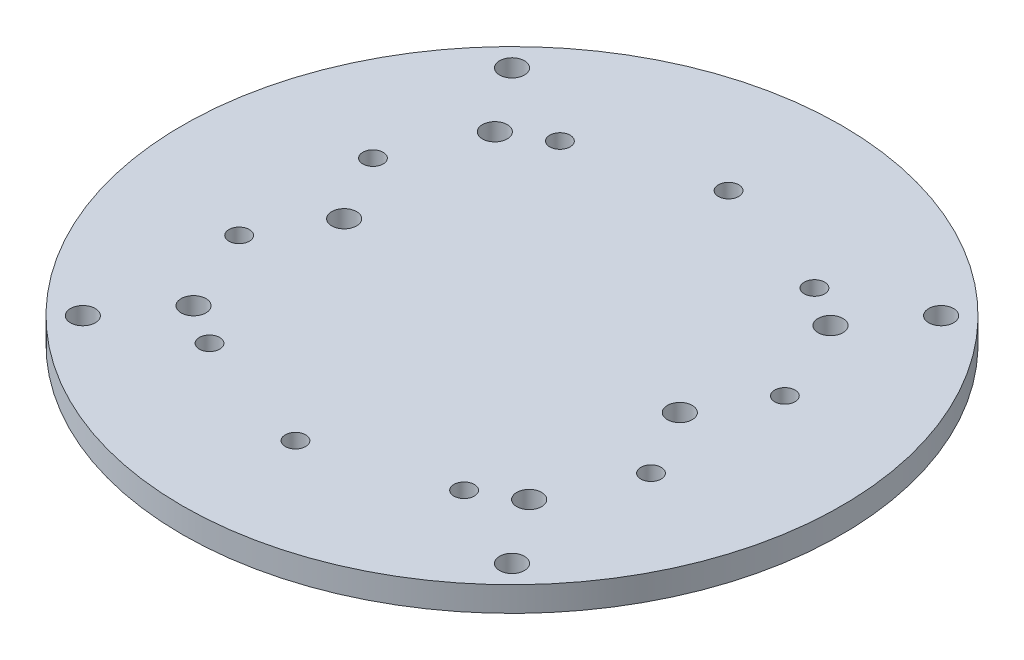
SolidWorks part; units mm, degrees
ref_plane "Front Plane" through (0, 0, 0) normal (0, 0, 1) x (1, 0, 0)
ref_plane "Top Plane" through (0, 0, 0) normal (0, 1, 0) x (1, 0, 0)
ref_plane "Right Plane" through (0, 0, 0) normal (1, 0, 0) x (0, 0, -1)
sketch "Sketch1" plane through (0, -66.8, 0) normal (0, -1, 0) x (1, 0, 0)
  circle A1 centre (0, 0) radius 84.1675 construction
  circle A3 centre (54.8008, 54.8008) radius 3.175
  circle A4 centre (54.8008, -54.8008) radius 3.175
  circle A5 centre (-54.8008, -54.8008) radius 3.175
  circle A6 centre (-54.8008, 54.8008) radius 3.175
  circle A7 centre (42.8625, -38.4762) radius 2.6035 construction
  circle A8 centre (42.8625, 0) radius 2.6035 construction
  circle A9 centre (42.8625, 38.4762) radius 2.6035 construction
  circle A10 centre (-42.8625, 38.4762) radius 2.6035 construction
  circle A11 centre (-42.8625, 0) radius 2.6035 construction
  circle A12 centre (-42.8625, -38.4762) radius 2.6035 construction
  circle A13 centre (42.8625, -38.4762) radius 2.6035 construction
  circle A14 centre (42.8625, 0) radius 2.6035 construction
  circle A15 centre (42.8625, 38.4762) radius 2.6035 construction
  circle A16 centre (-42.8625, 38.4762) radius 2.6035 construction
  circle A17 centre (-42.8625, 0) radius 2.6035 construction
  circle A18 centre (-42.8625, -38.4762) radius 2.6035 construction
  circle A19 centre (-42.8625, -38.4762) radius 3.175
  circle A20 centre (-42.8625, 0) radius 3.175
  circle A21 centre (-42.8625, 38.4762) radius 3.175
  circle A22 centre (42.8625, 38.4762) radius 3.175
  circle A23 centre (42.8625, 0) radius 3.175
  circle A24 centre (42.8625, -38.4762) radius 3.175
  circle A25 centre (-52.5982, -17.0902) radius 3.175 construction
  circle A26 centre (-52.5982, 17.0902) radius 3.175 construction
  circle A27 centre (-32.5075, 44.7427) radius 3.175 construction
  circle A28 centre (0, 55.305) radius 3.175 construction
  circle A29 centre (32.5075, 44.7427) radius 3.175 construction
  circle A30 centre (52.5982, 17.0902) radius 3.175 construction
  circle A31 centre (52.5982, -17.0902) radius 3.175 construction
  circle A32 centre (32.5075, -44.7427) radius 3.175 construction
  circle A33 centre (0, -55.305) radius 3.175 construction
  circle A34 centre (-32.5075, -44.7427) radius 3.175 construction
  circle A35 centre (-52.5982, -17.0902) radius 3.175 construction
  circle A36 centre (-52.5982, 17.0902) radius 3.175 construction
  circle A37 centre (-32.5075, 44.7427) radius 3.175 construction
  circle A38 centre (0, 55.305) radius 3.175 construction
  circle A39 centre (32.5075, 44.7427) radius 3.175 construction
  circle A40 centre (52.5982, 17.0902) radius 3.175 construction
  circle A41 centre (52.5982, -17.0902) radius 3.175 construction
  circle A42 centre (32.5075, -44.7427) radius 3.175 construction
  circle A43 centre (0, -55.305) radius 3.175 construction
  circle A44 centre (-32.5075, -44.7427) radius 3.175 construction
  circle A45 centre (-52.5982, -17.0902) radius 2.6035
  circle A46 centre (-52.5982, 17.0902) radius 2.6035
  circle A47 centre (-32.5075, 44.7427) radius 2.6035
  circle A48 centre (0, 55.305) radius 2.6035
  circle A49 centre (32.5075, 44.7427) radius 2.6035
  circle A50 centre (52.5982, 17.0902) radius 2.6035
  circle A51 centre (52.5982, -17.0902) radius 2.6035
  circle A52 centre (32.5075, -44.7427) radius 2.6035
  circle A53 centre (0, -55.305) radius 2.6035
  circle A54 centre (-32.5075, -44.7427) radius 2.6035
  circle A55 centre (54.8008, 54.8008) radius 3.175 construction
  circle A56 centre (54.8008, 54.8008) radius 3.175 construction
  circle A57 centre (0, 0) radius 84.1675
  point P15 (0, 0)
  dimension "D3" = 6.35
  dimension "D4" = 5.207
  dimension "D2" = 4
extrude "Boss-Extrude1" add sketch "Sketch1" along normal blind 6.35
